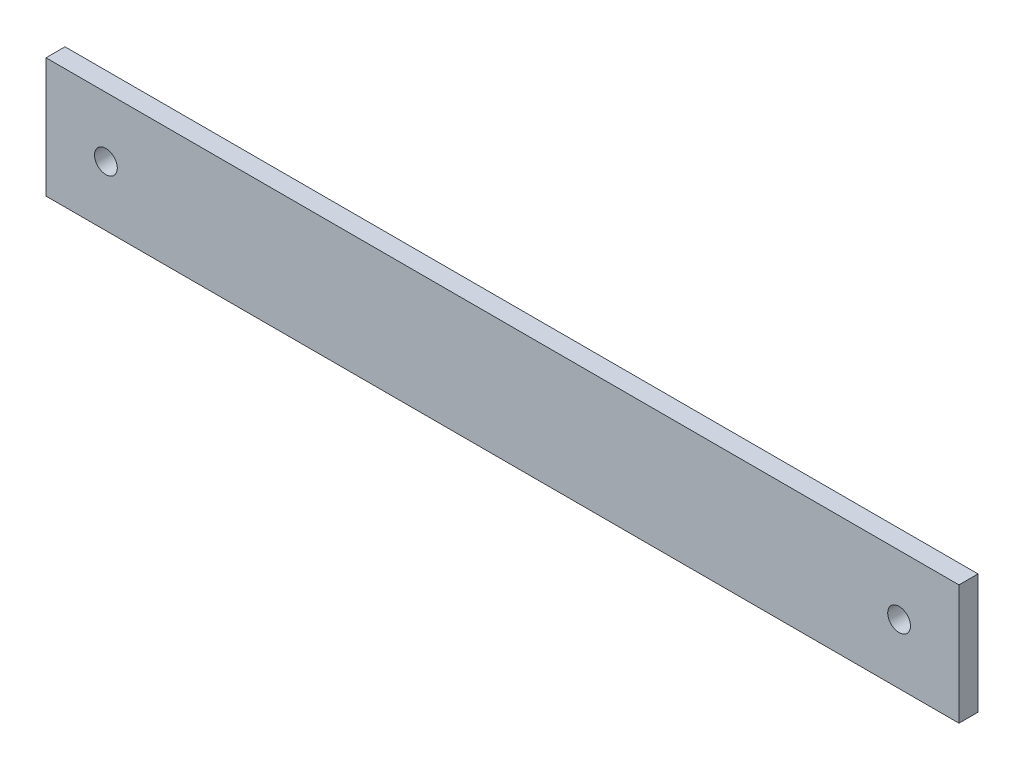
SolidWorks part; units mm, degrees
ref_plane "Front Plane" through (0, 0, 0) normal (0, 0, 1) x (1, 0, 0)
ref_plane "Top Plane" through (0, 0, 0) normal (0, 1, 0) x (1, 0, 0)
ref_plane "Right Plane" through (0, 0, 0) normal (1, 0, 0) x (0, 0, -1)
sketch "Sketch1" plane through (0, 0, 0) normal (0, 0, 1) x (1, 0, 0)
  line L1 (0, 0) -> (152.4, 0)
  line L2 (0, 0) -> (0, 20)
  line L3 (0, 20) -> (152.4, 20)
  line L4 (152.4, 0) -> (152.4, 20)
  dimension "D1" = 152.4
  dimension "D2" = 20
extrude "Boss-Extrude1" add sketch "Sketch1" along normal blind 3.175
hole_wizard "#6 Clearance Hole1" positions "Sketch3" profile "Sketch2" hole size "#6" standard "ANSI Inch"
sketch "Sketch3" plane through (0, 0, 0) normal (0, 0, -1) x (-1, 0, 0)
  line L0 (-152.4, 10) -> (0, 10) construction
  line L1 (-152.4, 0) -> (-152.4, 20) construction
  line L2 (0, 20) -> (0, 0) construction
  line L4 (-76.2, 0) -> (-76.2, 20) construction
  line L5 (0, 0) -> (-152.4, 0) construction
  line L6 (-152.4, 20) -> (0, 20) construction
  point P2 (-142.4, 10)
  point P21 (-10, 10)
  dimension "D1" = 10
sketch "Sketch2" plane through (142.4, 10, 0) normal (1, 0, 0) x (0, 1, 0)
  line L0 (0, 0) -> (0, 4.3148)
  line L1 (0, 4.3148) -> (1.8986, 3.174)
  line L2 (1.8986, 3.174) -> (1.8986, 0)
  line L5 (1.8986, 0) -> (0, 0)
  line L10 (0, 4.3148) -> (-1.8987, 3.174) construction
  line L11 (0, -6.35) -> (0, 107.95) construction
  dimension "Hole Dia." = 3.7973
  dimension "Hole Depth" = 3.174
  dimension "Drill Angle" = 118
